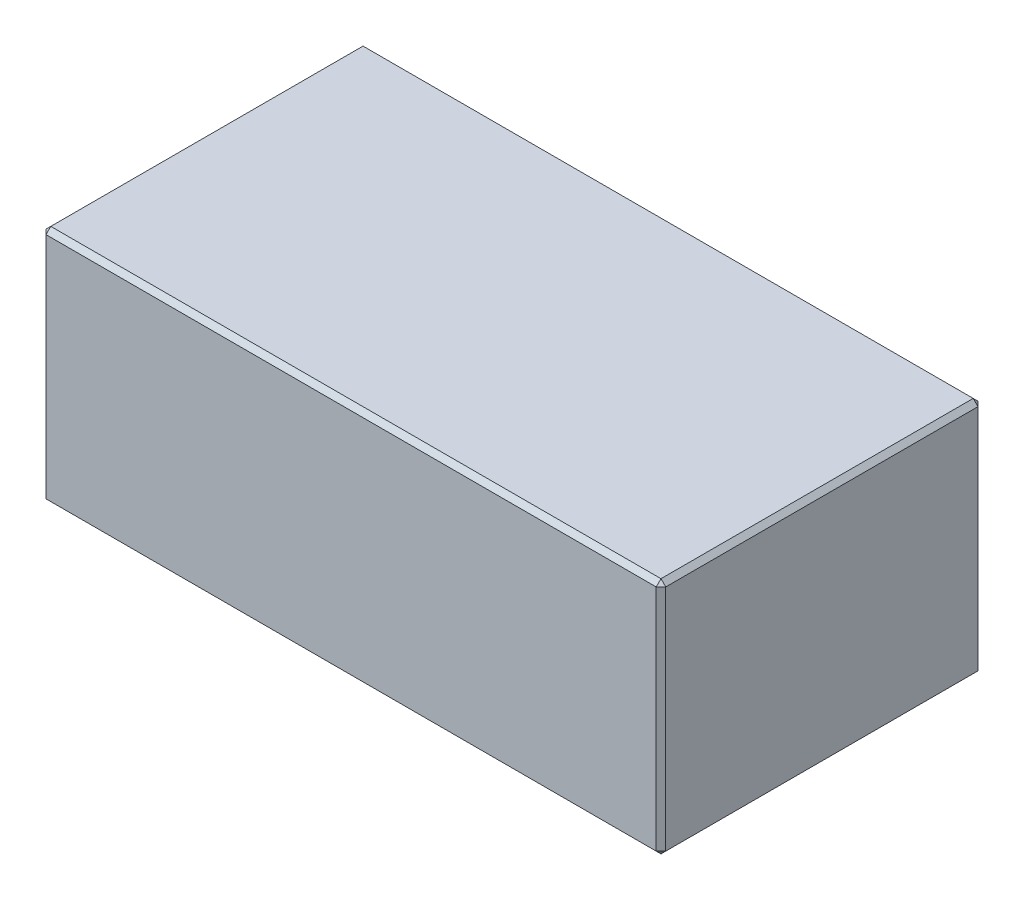
SolidWorks part; units mm, degrees
ref_plane "Front Plane" through (0, 0, 0) normal (0, 0, 1) x (1, 0, 0)
ref_plane "Top Plane" through (0, 0, 0) normal (0, 1, 0) x (1, 0, 0)
ref_plane "Right Plane" through (0, 0, 0) normal (1, 0, 0) x (0, 0, -1)
sketch "Sketch1" plane through (0, 0, 0) normal (0, 1, 0) x (1, 0, 0)
  line L1 (65, -33.75) -> (-65, -33.75)
  line L2 (65, -33.75) -> (65, 33.75)
  line L3 (65, 33.75) -> (-65, 33.75)
  line L4 (-65, -33.75) -> (-65, 33.75)
  line L5 (65, -33.75) -> (-65, 33.75) construction
  line L6 (65, 33.75) -> (-65, -33.75) construction
  point P0 (0, 0)
  dimension "D1" = 67.5
  dimension "D2" = 130
extrude "Boss-Extrude1" add sketch "Sketch1" along normal blind 50
chamfer "Chamfer1" distance 1 angle 45 12 edges at (65, 0, 0) (65, 25, -33.75) (0, 0, -33.75) (-65, 25, -33.75) (-65, 0, 0) (-65, 25, 33.75) (0, 0, 33.75) (65, 25, 33.75) (0, 50, -33.75) (65, 50, 0) (0, 50, 33.75) (-65, 50, 0)
